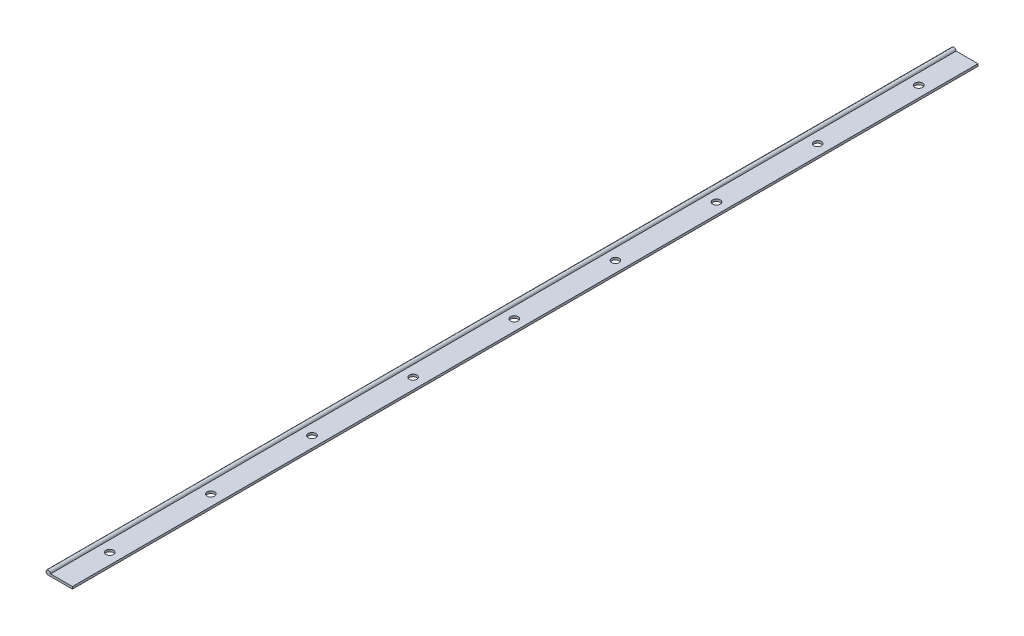
SolidWorks part; units mm, degrees
material "1.0037 (S235JR)"
ref_plane "Plan de face" through (0, 0, 0) normal (0, 0, 1) x (1, 0, 0)
ref_plane "Plan de dessus" through (0, 0, 0) normal (0, 1, 0) x (1, 0, 0)
ref_plane "Plan de droite" through (0, 0, 0) normal (1, 0, 0) x (0, 0, -1)
sketch "Esquisse1" plane through (0, 0, 0) normal (0, 0, 1) x (1, 0, 0)
  line L0 (16, -1.5) -> (0, -1.5)
  line L1 (1.5, 0) -> (16, 0)
  line L2 (16, 0) -> (16, -1.5)
  arc A0 (0, -1.5) -> (1.5, 0) centre (0, 0) cw
  dimension "D1" = 16
  dimension "D2" = 1.5
extrude "Boss.-Extru.1" add sketch "Esquisse1" along normal mid plane 600
sketch "Esquisse2" plane through (0, 0, 0) normal (0, 1, 0) x (1, 0, 0)
  line L0 (8.75, -300) -> (8.75, -268) construction
  line L1 (16, -300) -> (1.5, -300) construction
  circle A0 centre (8.75, -268) radius 2.5
  dimension "D1" = 5
  dimension "D2" = 32
extrude "Enlèv. mat.-Extru.1" cut sketch "Esquisse2" against normal through all
pattern_linear "Répétition linéaire1" count 9 spacing 67 along (0, 0, -1) of "Enlèv. mat.-Extru.1"
